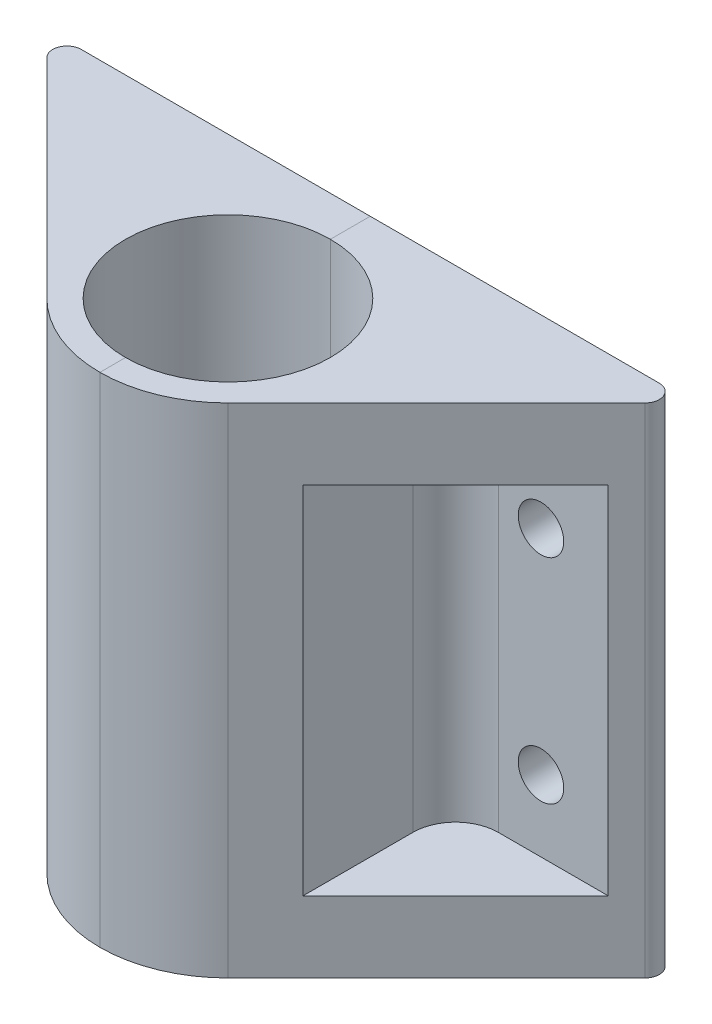
SolidWorks part; units mm, degrees
ref_plane "前视基准面" through (0, 0, 0) normal (0, 0, 1) x (1, 0, 0)
ref_plane "上视基准面" through (0, 0, 0) normal (0, 1, 0) x (1, 0, 0)
ref_plane "右视基准面" through (0, 0, 0) normal (1, 0, 0) x (0, 0, -1)
sketch "草图1" plane through (0, 0, 0) normal (0, 1, 0) x (1, 0, 0)
  circle A0 centre (0, 0) radius 9
  dimension "D1" = 18
extrude "凸台-拉伸1" add sketch "草图1" along normal blind 35
sketch "草图2" plane through (0, 35, 0) normal (0, 1, 0) x (1, 0, 0)
  circle A0 centre (0, 0) radius 7.2
  dimension "14.4" = 14.4
extrude "切除-拉伸1" cut sketch "草图2" against normal offset from surface (30 mm away) 5 up to face at (0, 0, 9)
sketch "草图3" plane through (0, 0, 0) normal (0, -1, 0) x (1, 0, 0)
  line L0 (0, 0) -> (0, -23.8994) construction
  line L1 (-6.364, 6.364) -> (-22.7279, -10)
  line L2 (-22.7279, -10) -> (22.7279, -10)
  line L3 (6.364, 6.364) -> (22.7279, -10)
  circle A0 centre (0, 0) radius 9 construction
  arc A1 (6.364, 6.364) -> (-6.364, 6.364) centre (0, 0) ccw
  circle A2 centre (0, 0) radius 7.2 construction
  circle A3 centre (0, 0) radius 7.2
  point P11 (0, -10)
  dimension "D1" = 10
  dimension "D2" = 45
extrude "凸台-拉伸2" add sketch "草图3" against normal up to surface (35 mm away) up to face at (0, 35, 7.2)
ref_plane "基准面1" through (0, 0, 9) normal (0, 0, 1) x (1, 0, 0)
sketch "草图4" plane through (0, 0, 9) normal (0, 0, 1) x (1, 0, 0)
  line L0 (0, 38.0624) -> (0, -10.8239) construction
  line L1 (-22.7279, 17.5) -> (39.5569, 17.5) construction
  line L2 (-22.7279, 35) -> (-22.7279, 0) construction
  line L3 (22.7279, 35) -> (22.7279, 0) construction
  line L4 (9, 5) -> (22.7279, 5)
  line L5 (9, 5) -> (9, 30)
  line L6 (9, 30) -> (22.7279, 30)
  line L7 (22.7279, 5) -> (22.7279, 30)
  line L8 (9, 5) -> (22.7279, 30) construction
  line L9 (9, 30) -> (22.7279, 5) construction
  line L10 (22.7279, 35) -> (6.364, 35) construction
  line L11 (-9, 30) -> (-22.7279, 30)
  line L12 (-22.7279, 5) -> (-22.7279, 30)
  line L13 (-9, 5) -> (-22.7279, 5)
  line L14 (-9, 5) -> (-9, 30)
  point P7 (15.864, 17.5)
  dimension "D1" = 5
  dimension "D2" = 18
extrude "切除-拉伸2" cut sketch "草图4" against normal offset from surface (16 mm away) 3 up to face at (0, 17.5, -10)
fillet "圆角1" radius 3 2 edges at (-9, 17.5, -7) (9, 17.5, -7)
sketch "草图5" plane through (0, 0, -7) normal (0, 0, 1) x (1, 0, 0)
  line L3 (0, 36.8683) -> (0, -5.9726) construction
  line L4 (-19.7279, 17.5) -> (-9, 17.5) construction
  line L5 (-19.7279, 30) -> (-19.7279, 5) construction
  line L6 (-9, 5) -> (-9, 30) construction
  circle A0 centre (-15, 25) radius 1.6
  circle A1 centre (-15, 10) radius 1.6
  circle A2 centre (15, 10) radius 1.6
  circle A3 centre (15, 25) radius 1.6
  dimension "D1" = 3.2
  dimension "D2" = 15
  dimension "D3" = 30
extrude "切除-拉伸3" cut sketch "草图5" against normal through all
sketch "草图6" plane through (0, 0, 0) normal (1, 0, 0) x (0, 0, -1)
  line L0 (10, 17.5) -> (-28.7092, 17.5) construction
  line L1 (10, 35) -> (10, 0) construction
  line L2 (-9, 35) -> (-9, 0) construction
  line L3 (-8.5, 28.4365) -> (-8.5, 24.5635)
  line L8 (-8.5, 6.5635) -> (-8.5, 10.4365)
  circle A0 centre (-12, 26.5) radius 1.6
  circle A1 centre (-12, 8.5) radius 1.6
  arc A3 (-8.5, 28.4365) -> (-8.5, 24.5635) centre (-12, 26.5) ccw
  arc A4 (-8.5, 6.5635) -> (-8.5, 10.4365) centre (-12, 8.5) cw
  dimension "D1" = 3.2
  dimension "D2" = 3
  dimension "D3" = 18
  dimension "D4" = 18.5
  dimension "D5" = 8
extrude "凸台-拉伸3" [suppressed] add sketch "草图6" along normal mid plane 5
fillet "圆角2" [suppressed] radius 3
fillet "圆角3" [suppressed] radius 1
fillet "圆角4" radius 1 2 edges at (22.7279, 17.5, -10) (-22.7279, 17.5, -10)
split "分割1" trim tools "右视基准面" bodies to split 110 111 resulting bodies 112 113
